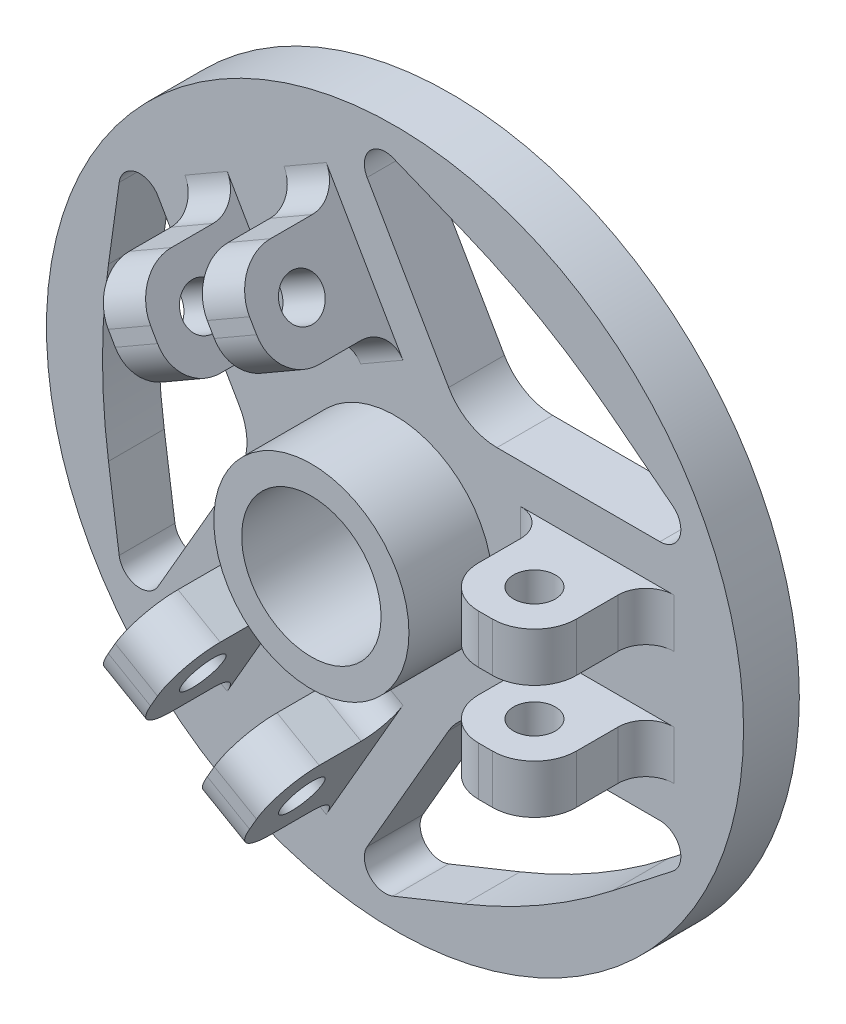
SolidWorks part; units mm, degrees
ref_plane "Front Plane" through (0, 0, 0) normal (0, 0, 1) x (1, 0, 0)
ref_plane "Top Plane" through (0, 0, 0) normal (0, 1, 0) x (1, 0, 0)
ref_plane "Right Plane" through (0, 0, 0) normal (1, 0, 0) x (0, 0, -1)
sketch "Sketch1" plane through (0, 0, 0) normal (0, 0, 1) x (1, 0, 0)
  circle A0 centre (0, 0) radius 25
  dimension "D1" = 50
extrude "Boss-Extrude1" add sketch "Sketch1" along normal blind 4
sketch "Sketch2" plane through (0, 0, 4) normal (0, 0, 1) x (1, 0, 0)
  circle A0 centre (0, 0) radius 5
  dimension "D1" = 10
extrude "Cut-Extrude1" cut sketch "Sketch2" against normal through all
sketch "Sketch3" plane through (0, 0, 4) normal (0, 0, 1) x (1, 0, 0)
  line L0 (0, 0) -> (25, 0) construction
  line L1 (11, -5.85) -> (18, -5.85)
  line L2 (11, 2.35) -> (18, 2.35)
  line L3 (11, 2.35) -> (11, 5.85)
  line L4 (11, 5.85) -> (18, 5.85)
  line L5 (18, 2.35) -> (18, 5.85)
  line L6 (18, -2.35) -> (18, -5.85)
  line L7 (11, -2.35) -> (18, -2.35)
  line L8 (11, -2.35) -> (11, -5.85)
  circle A0 centre (0, 0) radius 25 construction
  dimension "D1" = 3.5
  dimension "D2" = 2.35
  dimension "D3" = 11
  dimension "D4" = 7
extrude "Boss-Extrude2" add sketch "Sketch3" along normal blind 8
fillet "Fillet1" radius 3 4 edges at (11, -4.1, 12) (11, 4.1, 12) (18, -4.1, 12) (18, 4.1, 12)
sketch "Sketch4" plane through (0, 5.85, 0) normal (0, 1, 0) x (1, 0, 0)
  line L0 (15, -12) -> (14, -12) construction
  circle A0 centre (14.5, -8.5) radius 1.5
  point P4 (14.5, -12)
  dimension "D2" = 3
  dimension "D1" = 3.5
extrude "Cut-Extrude2" cut sketch "Sketch4" against normal through all
fillet "Fillet2" radius 2 4 edges at (11, -4.1, 4) (11, 4.1, 4) (18, -4.1, 4) (18, 4.1, 4)
pattern_circular "CirPattern1" count 3 over 360 about axis through (0, 0, 0) along (0, 0, 1) of "Boss-Extrude2", "Fillet1", "Cut-Extrude2", "Fillet2"
sketch "Sketch5" plane through (0, 0, 4) normal (0, 0, 1) x (1, 0, 0)
  circle A0 centre (0, 0) radius 5 construction
  circle A1 centre (0, 0) radius 5
  circle A2 centre (0, 0) radius 7
  dimension "D1" = 2
extrude "Boss-Extrude3" add sketch "Sketch5" along normal blind 6
sketch "Sketch6" plane through (0, 0, 4) normal (0, 0, 1) x (1, 0, 0)
  line L0 (0, 0) -> (25, 0) construction
  line L1 (-6.5352, 6.6192) -> (-2.4648, 8.9692) construction
  line L2 (0, 0) -> (-4.5, 7.7942) construction
  line L3 (0, 0) -> (12.5, 21.6506) construction
  line L4 (5, 8.6603) -> (-2, 20.7846)
  line L5 (-0.1391, 22.9254) -> (10.7062, 18.5436)
  line L10 (0.5662, 10.7192) -> (-4.9338, 20.2455) construction
  line L11 (5, 8.6603) -> (19, 8.6603)
  line L12 (19.9235, 11.3423) -> (10.7062, 18.5436)
  circle A0 centre (0, 0) radius 25 construction
  arc A1 (-2, 20.7846) -> (-0.1391, 22.9254) centre (-0.701, 21.5346) cw
  arc A2 (19, 8.6603) -> (19.9235, 11.3423) centre (19, 10.1603) ccw
  point P19 (-3.929, 24.5892)
  dimension "D5" = 1.5
  dimension "D1" = 120
  dimension "D2" = 60
  dimension "D3" = 38
  dimension "D4" = 14
  dimension "D6" = 10
extrude "Cut-Extrude3" cut sketch "Sketch6" against normal through all
fillet "Fillet3" radius 4 1 edges at (5, 8.6603, 2)
fillet "Fillet4" radius 44 1 edges at (10.7062, 18.5436, 2)
pattern_circular "CirPattern2" count 3 over 360 about axis through (0, 0, 0) along (0, 0, 1) of "Cut-Extrude3", "Fillet3", "Fillet4"
